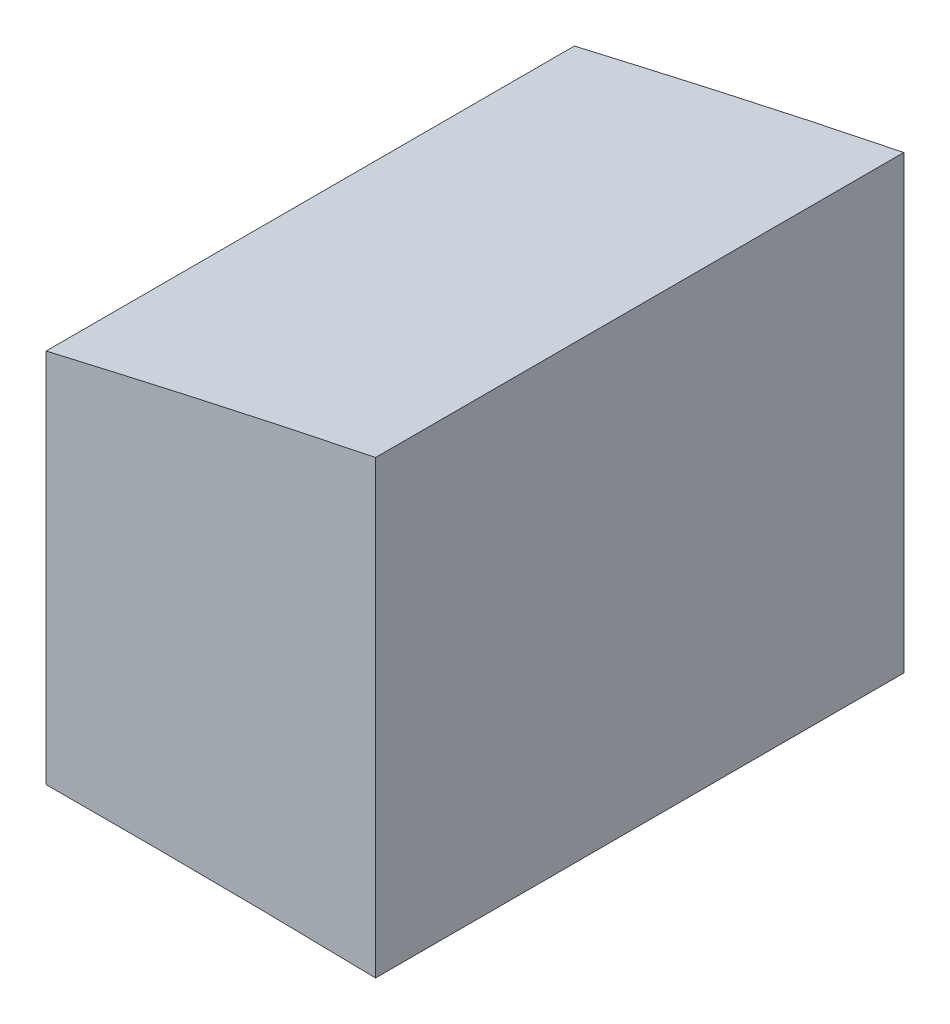
SolidWorks part; units mm, degrees
ref_plane "Front Plane" through (0, 0, 0) normal (0, 0, 1) x (1, 0, 0)
ref_plane "Top Plane" through (0, 0, 0) normal (0, 1, 0) x (1, 0, 0)
ref_plane "Right Plane" through (0, 0, 0) normal (1, 0, 0) x (0, 0, -1)
sketch "Sketch1" plane through (0, 0, 0) normal (0, 0, 1) x (1, 0, 0)
  line L0 (-66.007, 14.9523) -> (-66.007, -5.6347)
  circle A0 centre (63.517, -7.2283) radius 2.127
  circle A1 centre (-25.383, 13.0917) radius 2.127
  spline S0 degree 3 poles (76.217, -12.3083) (75.607, -6.7666) (69.7043, 1.1384) (56.4222, 10.2644) (36.9761, 19.3708) (8.7417, 24.8154) (-27.4552, 23.5667) (-52.3876, 18.1036) (-66.007, 14.9523) knots 0 0 0 0 0.086587 0.161737 0.268322 0.445157 0.638029 0.872371 0.872371 0.872371 0.872371
  spline S1 degree 3 poles (-66.007, -5.6347) (-44.594, -5.5392) (-13.013, -6.7241) (26.1367, -12.7509) (48.7653, -16.9008) (64.6834, -16.9691) (75.2906, -17.5225) (76.217, -12.3083) knots 0.133251 0.133251 0.133251 0.133251 0.51733 0.696667 0.84941 0.91952 1 1 1 1
extrude "Boss-Extrude1" add sketch "Sketch1" along normal blind 28.956
sketch "Sketch2" plane through (0, 0, 28.956) normal (0, 0, 1) x (1, 0, 0)
  line L1 (-47.9511, 30.6925) -> (167.5121, 30.6925)
  line L2 (-47.9511, 30.6925) -> (-47.9511, -22.6703)
  line L3 (-47.9511, -22.6703) -> (167.5121, -22.6703)
  line L4 (167.5121, 30.6925) -> (167.5121, -22.6703)
extrude "Cut-Extrude1" cut sketch "Sketch2" against normal blind 28.956
